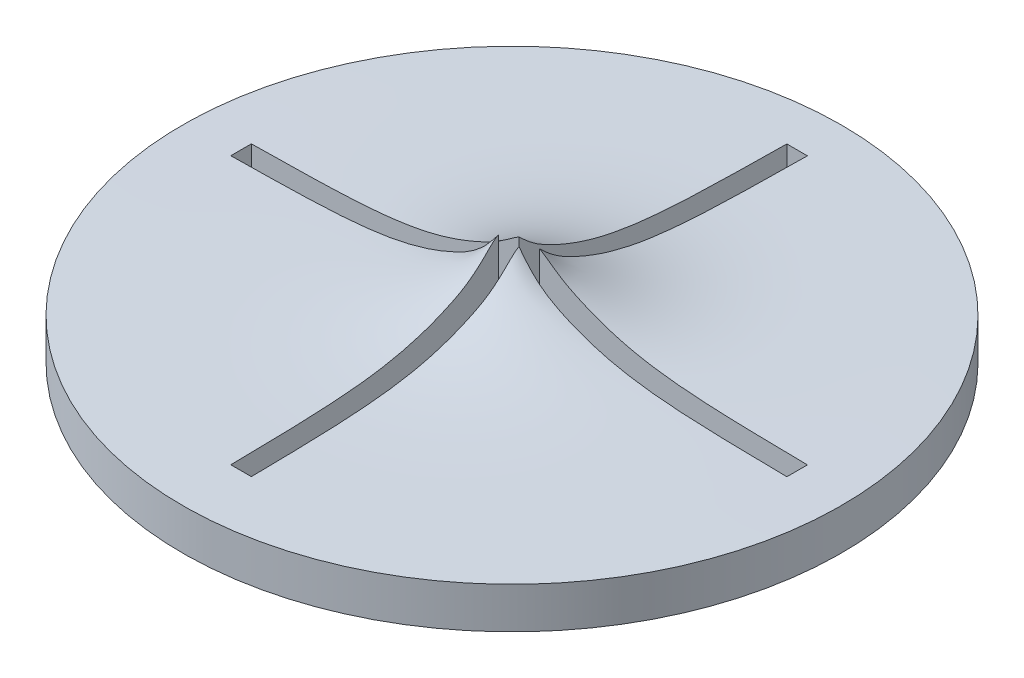
SolidWorks part; units mm, degrees
ref_plane "Front Plane" through (0, 0, 0) normal (0, 0, 1) x (1, 0, 0)
ref_plane "Top Plane" through (0, 0, 0) normal (0, 1, 0) x (1, 0, 0)
ref_plane "Right Plane" through (0, 0, 0) normal (1, 0, 0) x (0, 0, -1)
sketch "Sketch2" plane through (0, 0, 0) normal (0, 0, 1) x (1, 0, 0)
  line L2 (0, 1.0227) -> (0, 1.5227)
  line L4 (0, 1.0227) -> (0, 0) construction
  line L5 (0, 0) -> (4, 0) construction
  line L6 (4, 0) -> (4, 0.5)
  spline S0 degree 3 poles (4, 0) (2.193, 0.03) (1.2069, -0.0122) (0.2315, 0.5719) (0, 1.0227) knots 0 0 0 0 0.784164 1 1 1 1
  spline S1 degree 3 poles (4, 0.5) (2.193, 0.53) (1.2068, 0.4879) (0.2291, 1.0897) (0, 1.5227) knots 0 0 0 0 0.784164 1 1 1 1
  point P7 (0.3963, 0.5)
  point P8 (0, 0)
  point P11 (0, 0)
revolve "Revolve1" add sketch "Sketch2" angle 360 about L2
ref_plane "Plane1" through (0, 0, 0) normal (0, 1, 0) x (1, 0, 0)
sketch "Sketch3" plane through (0, 0, 0) normal (0, 1, 0) x (1, 0, 0)
  line L0 (0, 0) -> (0.125, 0) construction
  line L1 (0.125, -1.65) -> (0.125, -1.1002) construction
  line L2 (0, 0) -> (-0.125, 0) construction
  line L3 (-0.125, 0) -> (-0.125, 0.4607) construction
  line L4 (0, 0) -> (0, 0.2113) construction
  line L5 (-1.6132, 0.2113) -> (-1.0193, 0.2113) construction
  line L6 (0, 0) -> (0, -0.0387) construction
  line L7 (0, -0.0387) -> (0.4252, -0.0387) construction
  line L8 (-0.125, 0.2113) -> (-0.125, 3.4613)
  line L17 (-0.125, 3.4613) -> (0.125, 3.4613)
  line L18 (0.125, 3.4613) -> (0.125, 0.2113)
  line L19 (0.125, 0.2113) -> (3.375, 0.2113)
  line L20 (3.375, 0.2113) -> (3.375, -0.0387)
  line L21 (3.375, -0.0387) -> (0.125, -0.0387)
  line L22 (0.125, -0.0387) -> (0.125, -3.2887)
  line L23 (0.125, -3.2887) -> (-0.125, -3.2887)
  line L24 (-0.125, -3.2887) -> (-0.125, -0.0387)
  line L25 (-0.125, -0.0387) -> (-3.375, -0.0387)
  line L26 (-3.375, -0.0387) -> (-3.375, 0.2113)
  line L27 (-3.375, 0.2113) -> (-0.125, 0.2113)
extrude "Cut-Extrude1" cut sketch "Sketch3" along normal blind 2
